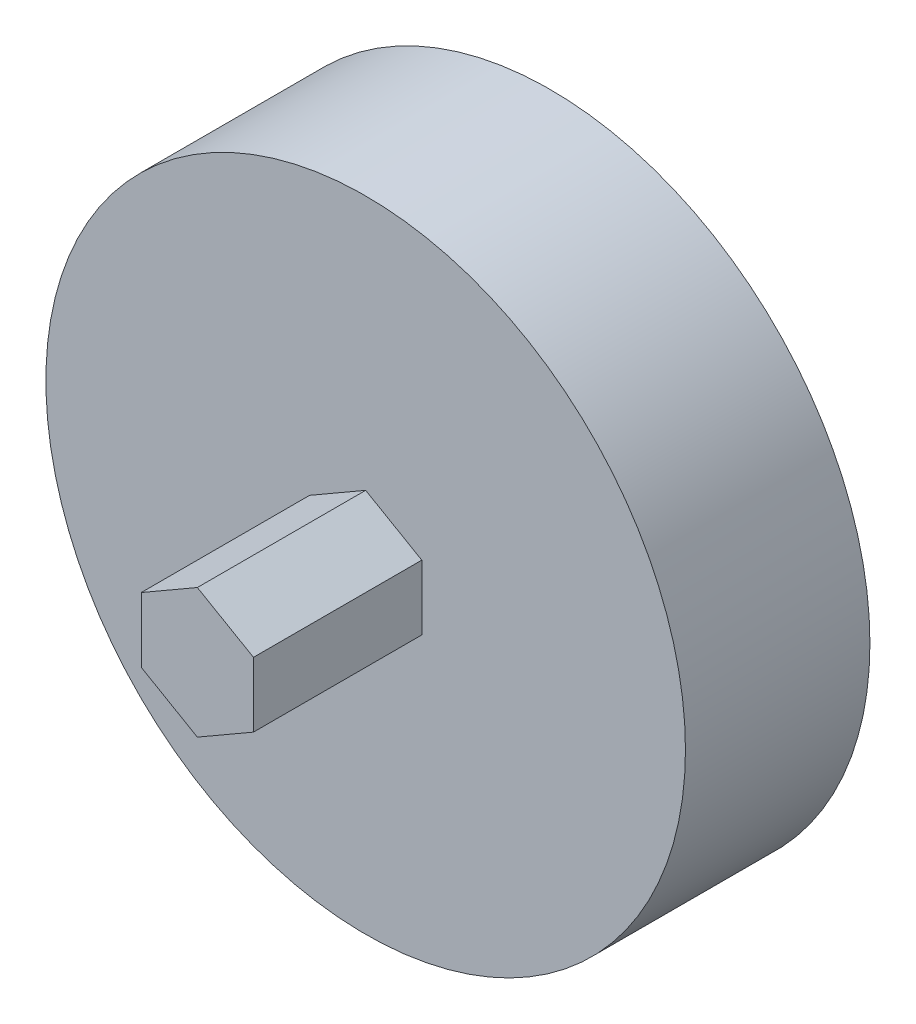
SolidWorks part; units mm, degrees
ref_plane "Front Plane" through (0, 0, 0) normal (0, 0, 1) x (1, 0, 0)
ref_plane "Top Plane" through (0, 0, 0) normal (0, 1, 0) x (1, 0, 0)
ref_plane "Right Plane" through (0, 0, 0) normal (1, 0, 0) x (0, 0, -1)
sketch "Sketch2" plane through (0, 0, 0) normal (0, 0, 1) x (1, 0, 0)
  circle A0 centre (0, 0) radius 36.195
  dimension "D1" = 72.39
extrude "Boss-Extrude1" add sketch "Sketch2" along normal blind 20.8788
sketch "Sketch3" plane through (0, 0, 20.8788) normal (0, 0, 1) x (1, 0, 0)
  line L1 (6.35, -3.6662) -> (6.35, 3.6662)
  line L2 (6.35, 3.6662) -> (0, 7.3323)
  line L3 (0, 7.3323) -> (-6.35, 3.6662)
  line L4 (-6.35, 3.6662) -> (-6.35, -3.6662)
  line L5 (-6.35, -3.6662) -> (0, -7.3323)
  line L6 (0, -7.3323) -> (6.35, -3.6662)
  circle A0 centre (0, 0) radius 6.35 construction
  point P1 (6.3362, 3.6899)
  point P10 (-6.35, 3.808)
  dimension "D1" = 12.7
extrude "Boss-Extrude2" add sketch "Sketch3" along normal blind 19.05
